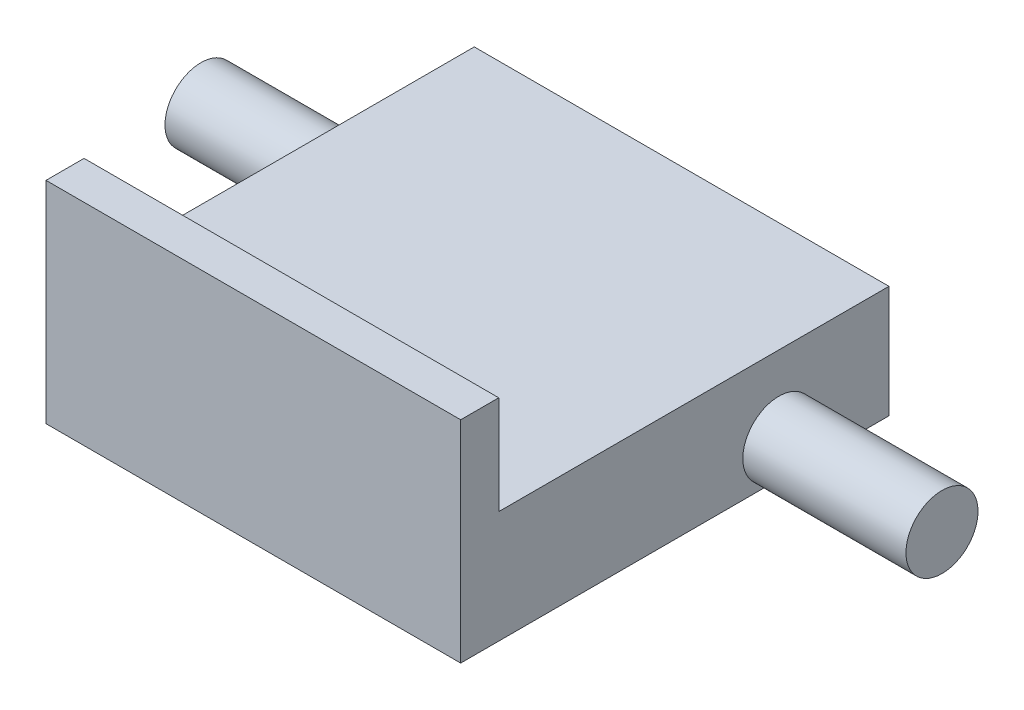
SolidWorks part; units mm, degrees
ref_plane "Face" through (0, 0, 0) normal (0, 0, 1) x (1, 0, 0)
ref_plane "Dessus" through (0, 0, 0) normal (0, 1, 0) x (1, 0, 0)
ref_plane "Droite" through (0, 0, 0) normal (1, 0, 0) x (0, 0, -1)
sketch "Esquisse2" plane through (0, 0, 0) normal (0, 0, 1) x (1, 0, 0)
  line L1 (-60.5877, 23.8172) -> (-30.0877, 23.8172)
  line L2 (-60.5877, 23.8172) -> (-60.5877, 15.5672)
  line L3 (-60.5877, 15.5672) -> (-30.0877, 15.5672)
  line L4 (-30.0877, 23.8172) -> (-30.0877, 15.5672)
  dimension "D1" = 30.5
  dimension "D2" = 8.25
extrude "Base-Extrusion" add sketch "Esquisse2" along normal blind 31.5
sketch "Esquisse3" plane through (0, 0, 31.5) normal (0, 0, 1) x (1, 0, 0)
  line L1 (-30.0877, 15.5672) -> (-60.5877, 15.5672)
  line L2 (-30.0877, 15.5672) -> (-30.0877, 31.0672)
  line L3 (-30.0877, 31.0672) -> (-60.5877, 31.0672)
  line L4 (-60.5877, 15.5672) -> (-60.5877, 31.0672)
  dimension "D1" = 15.5
extrude "Boss.-Extru.2" add sketch "Esquisse3" against normal blind 2.8
sketch "Esquisse4" plane through (-60.5877, 0, 0) normal (-1, 0, 0) x (0, 0, 1)
  line L0 (31.5, 31.0672) -> (31.5, 15.5672) construction
  line L1 (31.5, 15.5672) -> (0, 15.5672) construction
  circle A0 centre (8.1, 18.2172) radius 2.65
  dimension "D3" = 5.3
  dimension "D1" = 23.4
  dimension "D2" = 2.65
extrude "Boss.-Extru.3" add sketch "Esquisse4" along normal blind 12
ref_plane "Plan1" through (-45.3377, 0, 0) normal (-1, 0, 0) x (0, 0, 1)
mirror "Symétrie1" about plane through (-45.3377, 0, 0) normal (-1, 0, 0)
